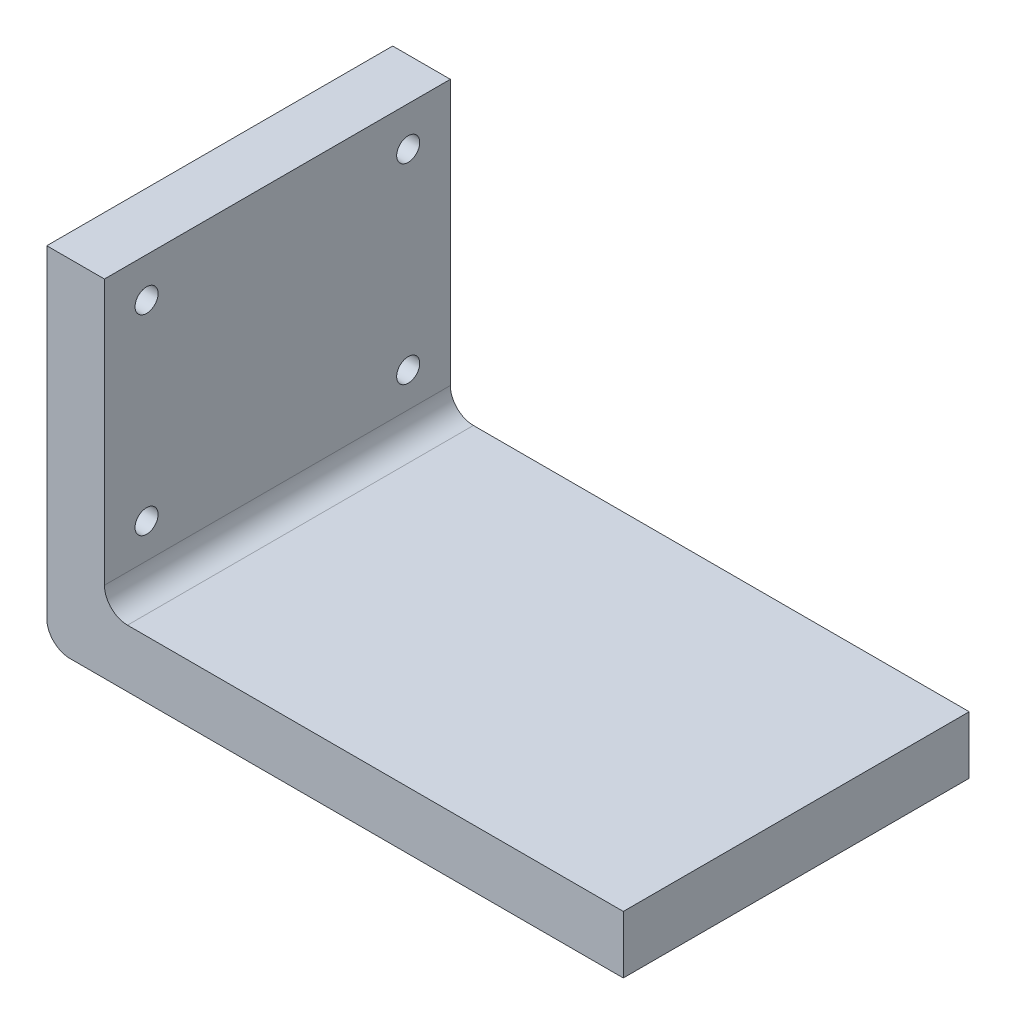
SolidWorks part; units mm, degrees
ref_plane "Front Plane" through (0, 0, 0) normal (0, 0, 1) x (1, 0, 0)
ref_plane "Top Plane" through (0, 0, 0) normal (0, 1, 0) x (1, 0, 0)
ref_plane "Right Plane" through (0, 0, 0) normal (1, 0, 0) x (0, 0, -1)
sketch "Sketch1" plane through (0, 0, 0) normal (0, 0, 1) x (1, 0, 0)
  line L0 (0, 5.08) -> (0, 76.2)
  line L4 (127, 12.7) -> (127, 0)
  line L5 (127, 0) -> (5.08, 0)
  line L6 (0, 76.2) -> (12.7, 76.2)
  line L7 (12.7, 76.2) -> (12.7, 17.78)
  line L8 (17.78, 12.7) -> (127, 12.7)
  arc A0 (5.08, 0) -> (0, 5.08) centre (5.08, 5.08) cw
  arc A1 (17.78, 12.7) -> (12.7, 17.78) centre (17.78, 17.78) cw
  point P9 (0, 0)
  dimension "D4" = 5.08
  dimension "D6" = 5.08
  dimension "D1" = 127
  dimension "D2" = 76.2
  dimension "D3" = 12.7
  dimension "D5" = 12.7
extrude "Boss-Extrude1" add sketch "Sketch1" along normal blind 76.2
sketch "Sketch4" plane through (0, 0, 0) normal (-1, 0, 0) x (0, 0, 1)
  line L0 (76.2, 76.2) -> (0, 76.2) construction
  circle A0 centre (9.2844, 67.5346) radius 2.54
  circle A1 centre (66.9156, 67.5346) radius 2.54
  circle A2 centre (66.9156, 25.4) radius 2.54
  circle A3 centre (9.2844, 25.4) radius 2.54
  point P0 (0, 0)
  point P22 (0, 0)
  point P23 (0, 0)
  point P24 (0, 0)
  point P25 (0, 0)
  point P26 (0, 0)
  point P27 (0, 0)
  point P28 (0, 0)
  point P29 (0, 0)
  dimension "D1" = 5.08
  dimension "D2" = 50.8
  dimension "D3" = 5.08
  dimension "D4" = 5.08
  dimension "D5" = 5.08
  dimension "D6" = 50.8
extrude "Cut-Extrude2" cut sketch "Sketch4" against normal blind 76.2
